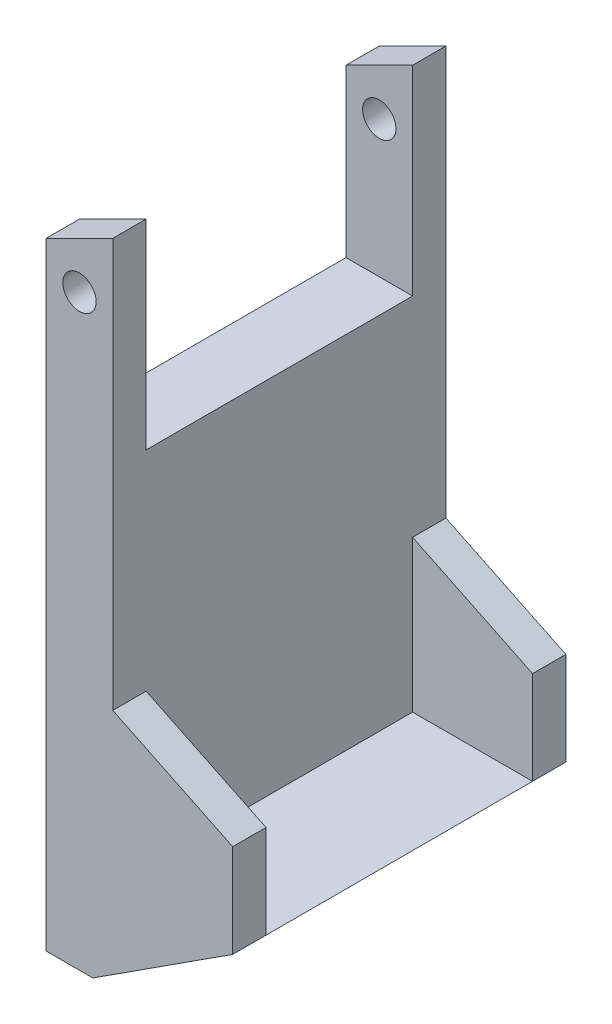
SolidWorks part; units mm, degrees
ref_plane "前视基准面" through (0, 0, 0) normal (0, 0, 1) x (1, 0, 0)
ref_plane "上视基准面" through (0, 0, 0) normal (0, 1, 0) x (1, 0, 0)
ref_plane "右视基准面" through (0, 0, 0) normal (1, 0, 0) x (0, 0, -1)
other "Configuration Table"
sketch "草图1" plane through (0, 0, 0) normal (1, 0, 0) x (0, 0, -1)
  line L1 (2.5, -5) -> (-2.5, -5)
  line L2 (2.5, -5) -> (2.5, 5)
  line L3 (2.5, 5) -> (-2.5, 5)
  line L4 (-2.5, -5) -> (-2.5, 5)
  line L5 (2.5, -5) -> (-2.5, 5) construction
  line L6 (2.5, 5) -> (-2.5, -5) construction
  point P0 (0, 0)
  dimension "D1" = 5
  dimension "D2" = 10
extrude "凸台-拉伸1" add sketch "草图1" along normal blind 8
sketch "草图2" plane through (0, 0, 2.5) normal (0, 0, 1) x (1, 0, 0)
  line L0 (0, 4.3541) -> (1, 5)
  line L3 (0, 5) -> (0, -5) construction
  line L4 (8, 5) -> (0, 5) construction
  line L5 (1, 5) -> (1, -0.6361)
  line L6 (1, -0.6361) -> (2.8, -1.5079)
  line L7 (2.8, -1.5079) -> (2.8, -2.9079)
  line L8 (2.8, -2.9079) -> (0.7, -4.2644)
  line L13 (0, -3.2692) -> (0, 4.3541)
  line L14 (0, -3.2692) -> (0, -4.2644)
  line L15 (0, -4.2644) -> (0.7, -4.2644)
  line M9 (0, 5) -> (0, -5)
  line M10 (0, -5) -> (8, -5)
  line M11 (8, -5) -> (8, 5)
  line M12 (8, 5) -> (0, 5)
  dimension "D1" = 1
  dimension "D2" = 2
  dimension "D3" = 0.7
  dimension "D4" = 1.4
  dimension "D5" = 2.8
  dimension "D6" = 2.5
extrude "切除-拉伸1" cut sketch "草图2" against normal blind 8 contours L15 L5 L6 L7 L8 M9 M10 M11 M12
sketch "草图3" plane through (0, 0, 2.5) normal (0, 0, 1) x (1, 0, 0)
  line L0 (1, 5) -> (1, 5.5)
  line L1 (1, 5.5) -> (0, 5)
  line L9 (0, -4.2644) -> (0.7, -4.2644)
  line L10 (0.7, -4.2644) -> (2.8, -2.9079)
  line L11 (2.8, -2.9079) -> (2.8, -1.5079)
  line L12 (2.8, -1.5079) -> (1, -0.6361)
  line L13 (1, -0.6361) -> (1, 5)
  line L14 (1, 5) -> (0, 5)
  line L15 (0, 5) -> (0, -4.2644)
  line L21 (1, 5) -> (0, 5)
  dimension "D1" = 0.5
  dimension "D2" = 0
extrude "凸台-拉伸2" add sketch "草图3" against normal blind 5
sketch "草图4" plane through (-2, 4, 0) normal (-0.4472, 0.8944, 0) x (0.8944, 0.4472, 0)
  line L0 (3.3541, 2.5) -> (3.3541, -2.5) construction
  line L1 (3.3541, 2) -> (2.2361, 2)
  line L2 (3.3541, 2) -> (3.3541, -2)
  line L3 (3.3541, -2) -> (2.2361, -2)
  line L4 (2.2361, 2) -> (2.2361, -2)
  line L5 (2.2361, 2.5) -> (2.2361, -2.5) construction
  line L6 (3.3541, 2.5) -> (2.2361, 2.5) construction
  line L7 (3.3541, -2.5) -> (2.2361, -2.5) construction
  dimension "D1" = 0.5
  dimension "D2" = 0.5
sketch "草图5" plane through (0, 0, 0) normal (-1, 0, 0) x (0, 0, 1)
  line L1 (2, 5) -> (-2, 5)
  line L2 (2, 5) -> (2, 2.5)
  line L3 (2, 2.5) -> (-2, 2.5)
  line L4 (-2, 5) -> (-2, 2.5)
  dimension "D1" = 4
  dimension "D2" = 2.5
extrude "切除-拉伸2" cut sketch "草图5" against normal blind 5
extrude "切除-拉伸3" cut sketch "草图4" against normal blind 5 contours L1 L4 L3 L2
sketch "草图7" plane through (-0.0595, -0.123, 0) normal (0.4359, 0.9, 0) x (0.9, -0.4359, 0)
  line L0 (1.1773, 2.5) -> (1.1773, -2.5) construction
  line L1 (1.1773, 2) -> (3.1773, 2)
  line L2 (1.1773, 2) -> (1.1773, -2)
  line L3 (1.1773, -2) -> (3.1773, -2)
  line L4 (3.1773, 2) -> (3.1773, -2)
  line L5 (3.1773, 2.5) -> (3.1773, -2.5) construction
  line L6 (1.1773, 2.5) -> (3.1773, 2.5) construction
  line L7 (1.1773, -2.5) -> (3.1773, -2.5) construction
  line L11 (3.1773, -2) -> (3.1773, 2)
  line L12 (3.1773, 2) -> (4.596, 2)
  dimension "D1" = 0.5
  dimension "D2" = 0.5
sketch "草图8" plane through (2.8, 0, 0) normal (1, 0, 0) x (0, 0, -1)
  line L0 (-2, -1.5079) -> (-2, -2.9079)
  line L1 (-2, -1.5079) -> (2, -1.5079)
  line L2 (-2, -2.9079) -> (2, -2.9079)
  line L3 (2, -1.5079) -> (2, -2.9079)
  line L4 (2.5, -2.9079) -> (-2.5, -2.9079) construction
  dimension "D1" = 4
extrude "切除-拉伸4" cut sketch "草图8" against normal up to vertex (1.8 mm away) up to point (1, -0.6361, 2.5)
sketch "草图10" plane through (0, -1.5079, 0) normal (0, -1, 0) x (1, 0, 0)
  line L1 (2.8, -2) -> (1, -2)
  line L2 (2.8, -2) -> (2.8, 2)
  line L3 (2.8, 2) -> (1, 2)
  line L4 (1, -2) -> (1, 2)
extrude "切除-拉伸5" cut sketch "草图10" against normal blind 2
sketch "草图11" plane through (0, 0, -2.5) normal (0, 0, -1) x (-1, 0, 0)
  line L0 (-0.5, 5.25) -> (-0.5, -4.7639) construction
  line L3 (-1, 5.5) -> (0, 5) construction
  line L5 (0, -4.2644) -> (0, 5) construction
  circle A0 centre (-0.5, 4.55) radius 0.25
  point P8 (0, 4.1911)
  dimension "D1" = 0.5
  dimension "D2" = 0.7
  dimension "D3" = 0.5
extrude "切除-拉伸6" cut sketch "草图11" against normal blind 10
